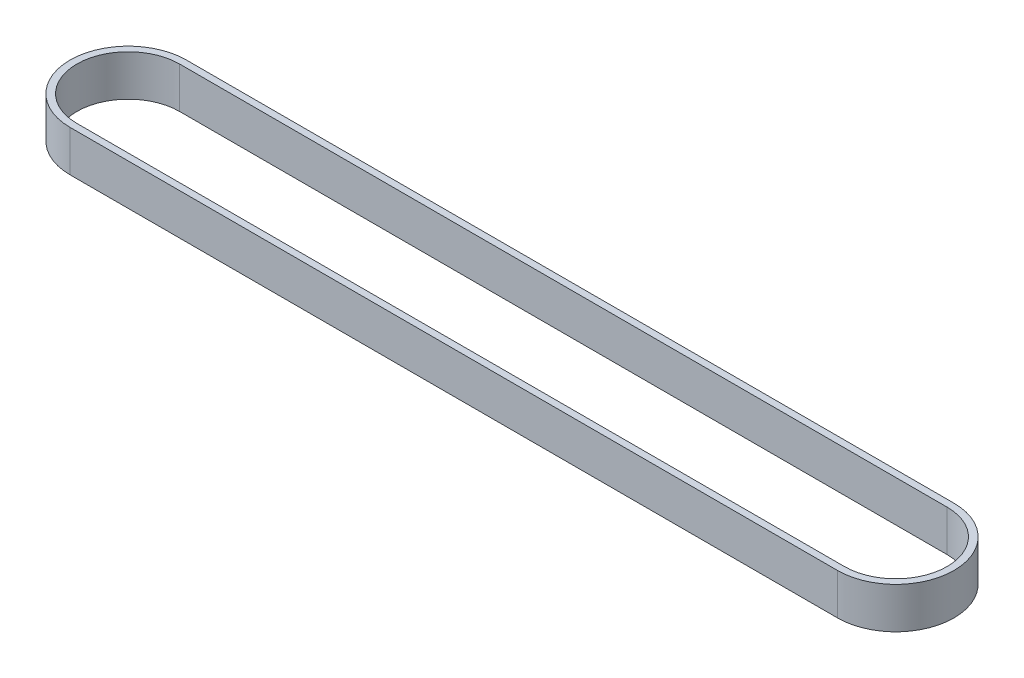
SolidWorks part; units mm, degrees
ref_plane "Front Plane" through (0, 0, 0) normal (0, 0, 1) x (1, 0, 0)
ref_plane "Top Plane" through (0, 0, 0) normal (0, 1, 0) x (1, 0, 0)
ref_plane "Right Plane" through (0, 0, 0) normal (1, 0, 0) x (0, 0, -1)
sketch "Sketch4" plane through (0, 0, 0) normal (0, 1, 0) x (1, 0, 0)
  line L0 (0, 0) -> (112, 0) construction
  line L1 (0, 7.5) -> (112, 7.5)
  line L2 (0, -7.5) -> (112, -7.5)
  line L3 (0, 0) -> (112, 0) construction
  line L4 (0, 8.5) -> (112, 8.5)
  line L5 (0, -8.5) -> (112, -8.5)
  arc A0 (0, 7.5) -> (0, -7.5) centre (0, 0) ccw
  arc A1 (112, -7.5) -> (112, 7.5) centre (112, 0) ccw
  arc A2 (0, 8.5) -> (0, -8.5) centre (0, 0) ccw
  arc A3 (112, -8.5) -> (112, 8.5) centre (112, 0) ccw
  point P3 (56, 0)
  point P10 (56, 0)
  dimension "D3" = 7.5
  dimension "D1" = 112
  dimension "D2" = 1
extrude "Boss-Extrude3" add sketch "Sketch4" along normal blind 6
